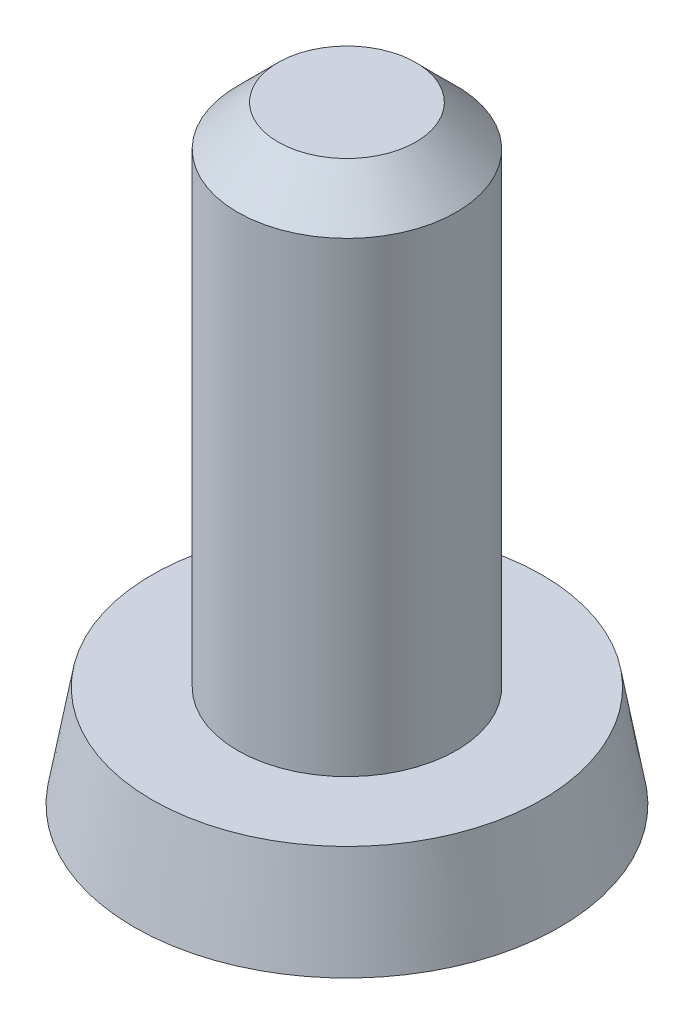
SolidWorks part; units mm, degrees
ref_plane "Front" through (0, 0, 0) normal (0, 0, 1) x (1, 0, 0)
ref_plane "Top" through (0, 0, 0) normal (0, 1, 0) x (1, 0, 0)
ref_plane "Right" through (0, 0, 0) normal (1, 0, 0) x (0, 0, -1)
sketch "Sketch1" plane through (0, 0, 0) normal (0, 1, 0) x (1, 0, 0)
  circle A0 centre (0, 0) radius 2.667
  dimension "D1" = 5.334
extrude "Boss-Extrude1" add sketch "Sketch1" along normal blind 1.27 draft 10
sketch "Sketch2" plane through (0, 0, 0) normal (1, 0, 0) x (0, 0, -1)
  line L0 (0, 0) -> (0, -0.762)
  line L1 (0, 0) -> (-2.667, 0)
  arc A0 (-2.667, 0) -> (0, -0.762) centre (-0.0196, 4.2178) ccw
  dimension "D2" = 4.9798
  dimension "D1" = 0.762
revolve "Revolve1" add sketch "Sketch2" angle 360 about L0
sketch "Sketch3" plane through (0, 1.27, 0) normal (0, 1, 0) x (1, 0, 0)
  circle A0 centre (0, 0) radius 1.3716
  dimension "D1" = 2.7432
extrude "Boss-Extrude2" add sketch "Sketch3" along normal blind 6.35
chamfer "Chamfer1" distance 0.508 angle 45 1 edges at (0, 7.62, 1.3716)
ref_plane "Plane1" through (0, -2.54, 0) normal (0, 1, 0) x (1, 0, 0)
sketch "Sketch4" plane through (0, -2.54, 0) normal (0, 1, 0) x (1, 0, 0)
  line L0 (-1.651, 0.381) -> (-1.651, -0.381)
  line L1 (-1.651, -0.381) -> (-0.381, -0.381)
  line L2 (-0.381, -0.381) -> (-0.381, -1.651)
  line L3 (-0.381, -1.651) -> (0.381, -1.651)
  line L4 (0.381, -1.651) -> (0.381, -0.381)
  line L5 (0.381, -0.381) -> (1.651, -0.381)
  line L6 (1.651, -0.381) -> (1.651, 0.381)
  line L7 (1.651, 0.381) -> (0.381, 0.381)
  line L8 (0.381, 0.381) -> (0.381, 1.651)
  line L9 (0.381, 1.651) -> (-0.381, 1.651)
  line L10 (-0.381, 1.651) -> (-0.381, 0.381)
  line L11 (-0.381, 0.381) -> (-1.651, 0.381)
  line L12 (-1.651, 0) -> (0, 0) construction
  line L13 (0, 0) -> (1.651, 0) construction
  line L14 (0, 1.651) -> (0, 0) construction
  line L15 (0, 0) -> (0, -1.651) construction
  dimension "D1" = 0.762
  dimension "D2" = 1.27
extrude "Cut-Extrude5" cut sketch "Sketch4" along normal blind 3.048
fillet "Fillet1" radius 0.635 4 edges at (0.381, -0.1134, -0.381) (-0.381, -0.1134, -0.381) (0.381, -0.1134, 0.381) (-0.381, -0.1134, 0.381)
